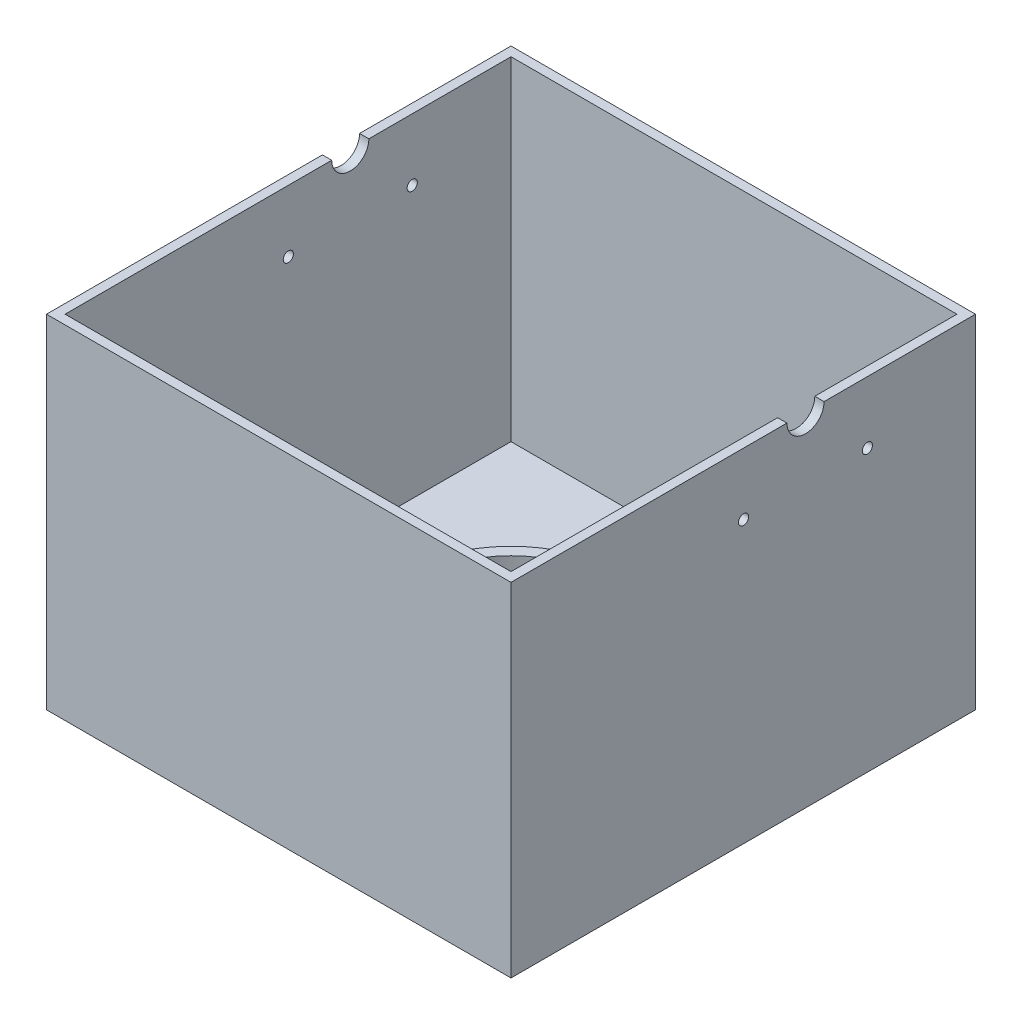
SolidWorks part; units mm, degrees
other "标注1"
sketch "草图10" plane through (-75, 110.65, 75) normal (-0.0015, 0.991, 0.1342) x (0.9966, 0.0125, -0.0811)
ref_plane "前视基准面" through (0, 0, 0) normal (0, 0, 1) x (1, 0, 0)
ref_plane "上视基准面" through (0, 0, 0) normal (0, 1, 0) x (1, 0, 0)
ref_plane "右视基准面" through (0, 0, 0) normal (1, 0, 0) x (0, 0, -1)
sketch "草图1" plane through (0, 0, 0) normal (0, 1, 0) x (1, 0, 0)
  line L1 (-75, 75) -> (75, 75)
  line L2 (-75, 75) -> (-75, -75)
  line L3 (-75, -75) -> (75, -75)
  line L4 (75, 75) -> (75, -75)
  line L5 (-75, 75) -> (75, -75) construction
  line L6 (-75, -75) -> (75, 75) construction
  point P0 (0, 0)
  dimension "D1" = 150
  dimension "D2" = 150
extrude "凸台-拉伸1" add sketch "草图1" along normal blind 3
sketch "草图2" plane through (0, 3, 0) normal (0, 1, 0) x (1, 0, 0)
  line L1 (75, -75) -> (-75, -75)
  line L2 (75, -75) -> (75, 75)
  line L3 (75, 75) -> (-75, 75)
  line L4 (-75, -75) -> (-75, 75)
  line L5 (75, -75) -> (-75, 75) construction
  line L6 (75, 75) -> (-75, -75) construction
  line L7 (72, -72) -> (-72, -72)
  line L8 (72, -72) -> (72, 72)
  line L9 (72, 72) -> (-72, 72)
  line L10 (-72, -72) -> (-72, 72)
  line L11 (72, -72) -> (-72, 72) construction
  line L12 (72, 72) -> (-72, -72) construction
  point P0 (0, 0)
  point P7 (0, 0)
  dimension "D1" = 144
extrude "凸台-拉伸2" add sketch "草图2" along normal blind 107.65
sketch "草图3" plane through (0, 0, 0) normal (0, -1, 0) x (1, 0, 0)
  circle A0 centre (0, 0) radius 31.25
  dimension "D1" = 62.5
extrude "切除-拉伸1" cut sketch "草图3" against normal blind 91
sketch "草图4" plane through (-75, 0, 0) normal (-1, 0, 0) x (0, 0, 1)
  line L0 (-75, 110.65) -> (75, 110.65) construction
  line L1 (-75, 110.65) -> (-75, 0) construction
  circle A0 centre (-20.1, 110.65) radius 6
  dimension "D1" = 12
  dimension "D2" = 54.9
extrude "切除-拉伸2" cut sketch "草图4" against normal through all
sketch "草图8" plane through (0, 3, 0) normal (0, 1, 0) x (1, 0, 0)
  circle A0 centre (0, 0) radius 31.25
  circle A1 centre (0, 0) radius 35
  dimension "D1" = 62.5
  dimension "D2" = 70
extrude "凸台-拉伸4" add sketch "草图8" along normal blind 18
sketch "草图9" plane through (-75, 0, 0) normal (-1, 0, 0) x (0, 0, 1)
  line L0 (-20.1, 104.65) -> (-20.1, 66.4211) construction
  line L2 (-75, 110.65) -> (-26.1, 110.65) construction
  arc A0 (-26.1, 110.65) -> (-14.1, 110.65) centre (-20.1, 110.65) ccw construction
  circle A1 centre (-40.1, 90.65) radius 1.65
  circle A2 centre (-0.1, 90.65) radius 1.65
  dimension "D1" = 3.3
  dimension "D2" = 3.3
  dimension "D3" = 40
  dimension "D4" = 20
extrude "切除-拉伸3" cut sketch "草图9" against normal through all
sketch "草图14" plane through (0, 0, 0) normal (0, -1, 0) x (1, 0, 0)
  circle A0 centre (0, 0) radius 31.25
  circle A1 centre (0, 0) radius 35
  dimension "D1" = 70
  dimension "D2" = 62.5
extrude "凸台-拉伸7" add sketch "草图14" along normal blind 27
sketch "草图15" plane through (0, -27, 0) normal (0, -1, 0) x (1, 0, 0)
  circle A0 centre (0, 0) radius 31.25
  circle A1 centre (0, 0) radius 27.5
  dimension "D1" = 62.5
  dimension "D2" = 55
extrude "凸台-拉伸8" add sketch "草图15" against normal blind 3
